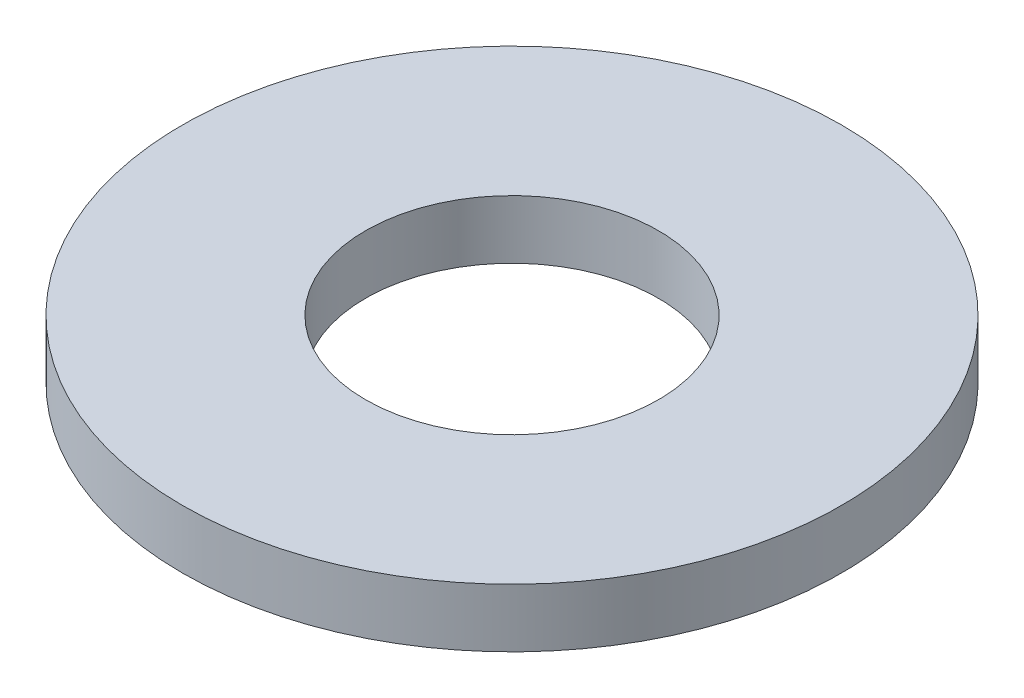
SolidWorks part; units mm, degrees
ref_plane "正面" through (0, 0, 0) normal (0, 0, 1) x (1, 0, 0)
ref_plane "平面" through (0, 0, 0) normal (0, 1, 0) x (1, 0, 0)
ref_plane "右側面" through (0, 0, 0) normal (1, 0, 0) x (0, 0, -1)
sketch "ｽｹｯﾁ1" plane through (0, 0, 0) normal (0, 1, 0) x (1, 0, 0)
  circle A0 centre (0, 0) radius 4
  circle A1 centre (0, 0) radius 9
  dimension "D1" = 18
  dimension "D2" = 8
extrude "ﾎﾞｽ - 押し出し1" add sketch "ｽｹｯﾁ1" along normal blind 1.6
